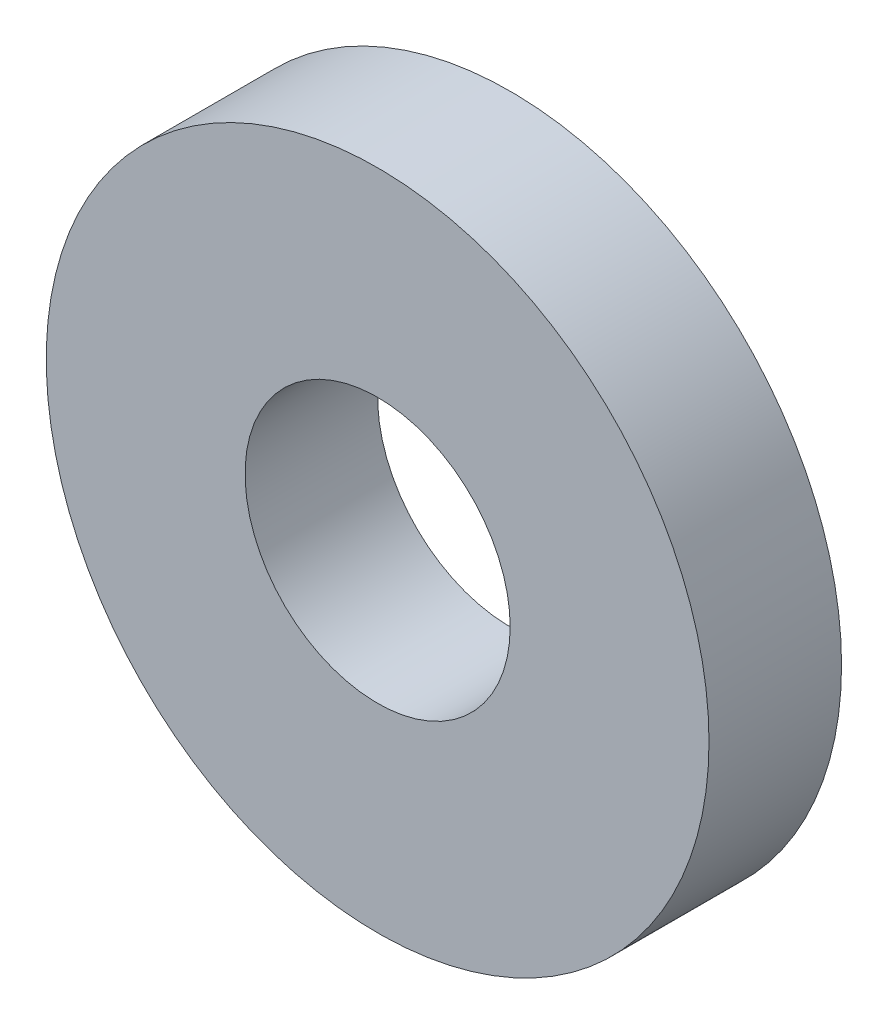
SolidWorks part; units mm, degrees
ref_plane "Front Plane" through (0, 0, 0) normal (0, 0, 1) x (1, 0, 0)
ref_plane "Top Plane" through (0, 0, 0) normal (0, 1, 0) x (1, 0, 0)
ref_plane "Right Plane" through (0, 0, 0) normal (1, 0, 0) x (0, 0, -1)
sketch "Sketch1" plane through (0, 0, 0) normal (0, 0, 1) x (1, 0, 0)
  circle A0 centre (0, 0) radius 25
  circle A1 centre (0, 0) radius 10
  dimension "D1" = 50
  dimension "D2" = 20
extrude "Boss-Extrude1" add sketch "Sketch1" along normal blind 10
